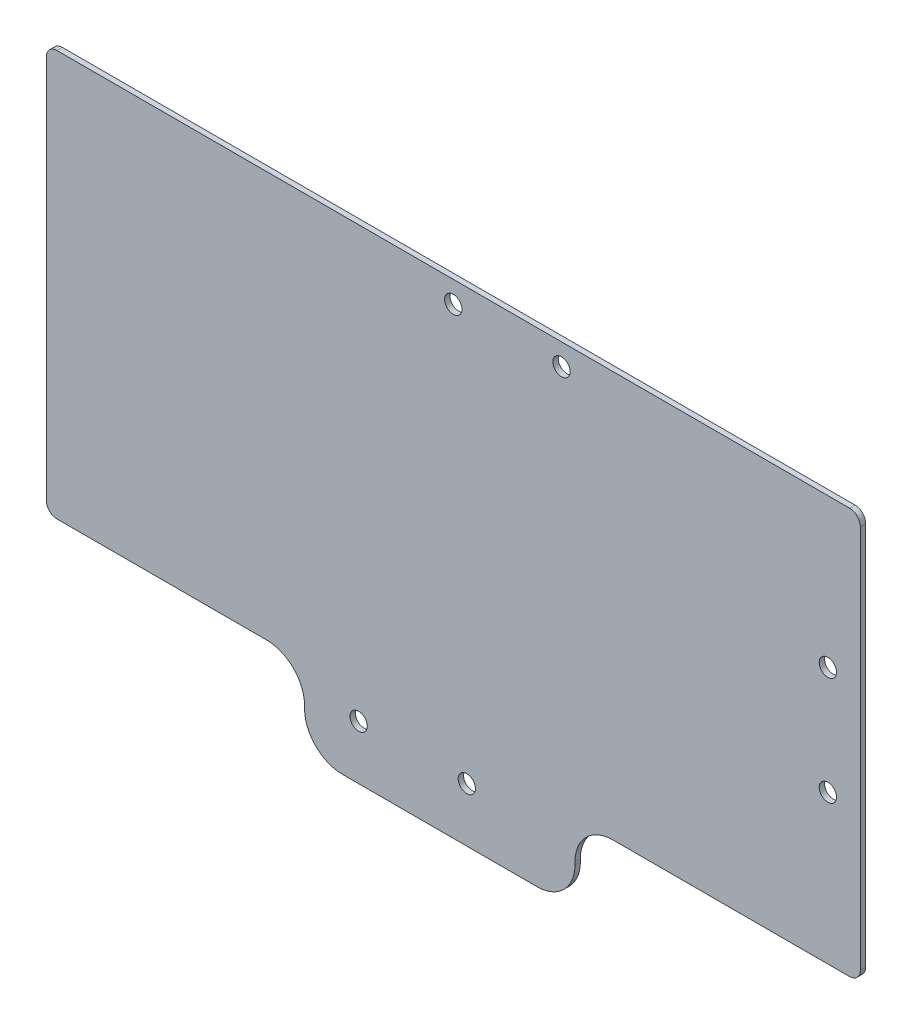
SolidWorks part; units mm, degrees
material "Thornel Mat VMA"
ref_plane "前视基准面" through (0, 0, 0) normal (0, 0, 1) x (1, 0, 0)
ref_plane "上视基准面" through (0, 0, 0) normal (0, 1, 0) x (1, 0, 0)
ref_plane "右视基准面" through (0, 0, 0) normal (1, 0, 0) x (0, 0, -1)
other "Configuration Table"
sketch "草图1" plane through (0, 0, 0) normal (0, 0, 1) x (1, 0, 0)
  line L0 (-10, 0) -> (10, 0) construction
  line L1 (0, 0) -> (0, -50000) construction
  line L3 (-30, -10) -> (30, -10)
  line L4 (-30, -10) -> (-30, 4.5)
  line L5 (-30, 4.5) -> (30, 4.5)
  line L6 (30, -10) -> (30, 4.5)
  line L7 (-30, -10) -> (30, 4.5) construction
  line L8 (-30, 4.5) -> (30, -10) construction
  circle A0 centre (-10, 0) radius 1.6
  circle A1 centre (10, 0) radius 1.6
  point P4 (0, 0)
  point P9 (0, -2.75)
  dimension "D1" = 3.2
  dimension "D2" = 20
  dimension "D3" = 4.5
  dimension "D4" = 60
  dimension "D5" = 10
extrude "凸台-拉伸1" add sketch "草图1" along normal blind 1
sketch "草图2" plane through (0, 0, 0) normal (0, 0, -1) x (-1, 0, 0)
  line L0 (-30, 4.5) -> (30, 4.5) construction
  line L1 (-82.75, 4.5) -> (37.75, 4.5)
  line L2 (-82.75, 4.5) -> (-82.75, 79.5)
  line L3 (-82.75, 79.5) -> (37.75, 79.5)
  line L4 (37.75, 4.5) -> (37.75, 79.5)
  line L5 (-76.75, 79.5) -> (-76.75, 4.5) construction
  line L6 (-79.75, 42) -> (49920.25, 42) construction
  circle A0 centre (-10, 0) radius 1.6 construction
  circle A1 centre (-76.75, 52) radius 1.6
  circle A2 centre (-76.75, 32) radius 1.6
  point P12 (-76.75, 42)
  dimension "D4" = 3.2
  dimension "D5" = 20
  dimension "D6" = 47.75
  dimension "D1" = 72.75
  dimension "D2" = 75
  dimension "D3" = 6
extrude "凸台-拉伸2" add sketch "草图2" against normal blind 1
sketch "草图3" plane through (0, 0, 0) normal (0, 0, -1) x (-1, 0, 0)
  line L1 (-82.75, 79.5) -> (37.75, 79.5) construction
  line L2 (-82.75, 75.5) -> (37.75, 75.5) construction
  line L3 (-82.75, 79.5) -> (-82.75, 4.5) construction
  line L4 (37.75, 4.5) -> (37.75, 79.5) construction
  line L5 (-22.5, 75.5) -> (-22.5, -49924.5) construction
  circle A0 centre (-27.5, 75.5) radius 1.6
  circle A1 centre (-7.5, 75.5) radius 1.6
  point P16 (-22.5, 75.5)
  dimension "D2" = 20
  dimension "D3" = 3.2
  dimension "D4" = 5
  dimension "D1" = 4
extrude "切除-拉伸1" cut sketch "草图3" against normal blind 10
sketch "草图4" plane through (0, 0, 0) normal (0, 0, -1) x (-1, 0, 0)
  line L0 (30, 4.5) -> (37.75, 4.5) construction
  line L1 (37.75, 79.5) -> (67.75, 79.5)
  line L2 (37.75, 79.5) -> (37.75, 4.5)
  line L3 (37.75, 4.5) -> (67.75, 4.5)
  line L4 (67.75, 79.5) -> (67.75, 4.5)
  line L5 (37.75, 4.5) -> (37.75, 79.5) construction
  dimension "D1" = 30
extrude "凸台-拉伸3" add sketch "草图4" against normal up to surface (1 mm away) up to face at (25.9, 75.5, 1)
fillet "圆角1" radius 7 2 edges at (30, -10, 0.5) (30, 4.5, 0.5)
sketch "草图5" plane through (0, 0, 0) normal (0, 0, -1) x (-1, 0, 0)
  line L0 (30, -10) -> (-23, -10) construction
  line L1 (30, 4.5) -> (20, 4.5)
  line L2 (30, 4.5) -> (30, -10)
  line L3 (30, -10) -> (20, -10)
  line L4 (20, 4.5) -> (20, -10)
  dimension "D1" = 10
extrude "切除-拉伸2" cut sketch "草图5" against normal blind 10
fillet "圆角2" radius 7 2 edges at (-20, -10, 0.5) (-20, 4.5, 0.5)
fillet "圆角3" radius 2 4 edges at (-67.75, 4.5, 0.5) (82.75, 4.5, 0.5) (-67.75, 79.5, 0.5) (82.75, 79.5, 0.5)
